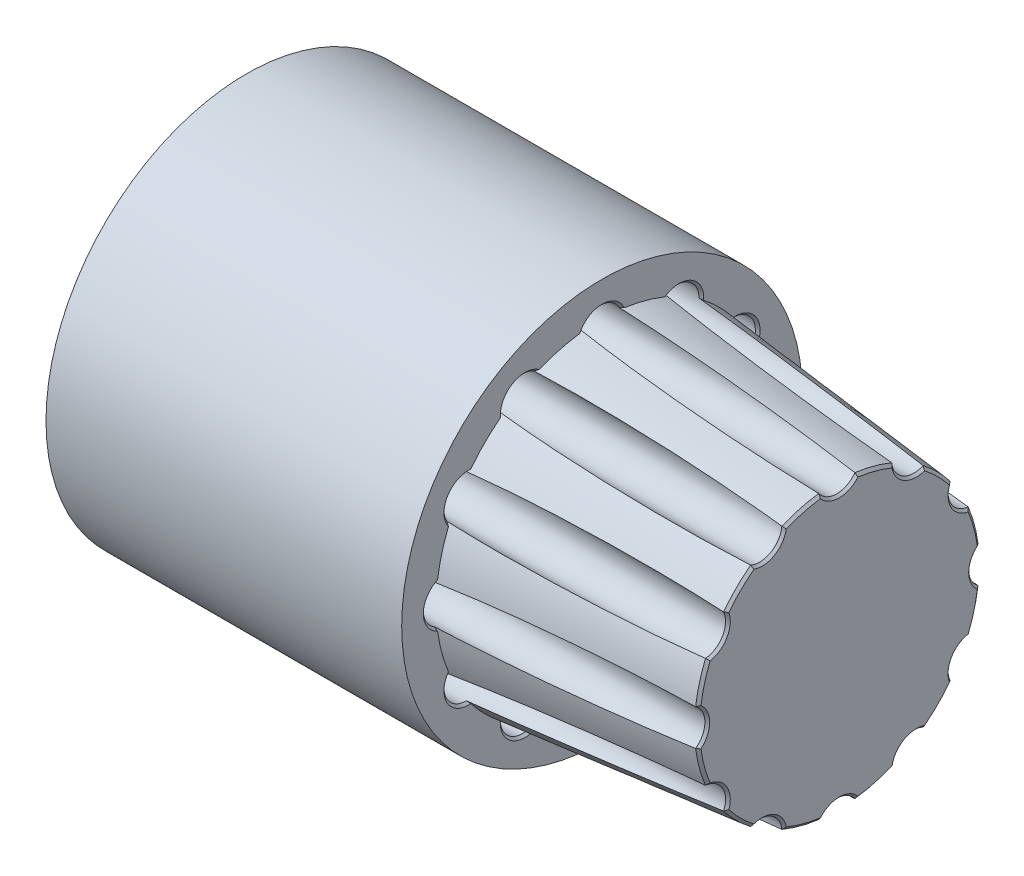
SolidWorks part; units mm, degrees
material "AISI 4340 Steel, normalized"
ref_plane "Front" through (0, 0, 0) normal (0, 0, 1) x (1, 0, 0)
ref_plane "Top" through (0, 0, 0) normal (0, 1, 0) x (1, 0, 0)
ref_plane "Right" through (0, 0, 0) normal (1, 0, 0) x (0, 0, -1)
sketch "Sketch1" plane through (0, 0, 0) normal (1, 0, 0) x (0, 0, -1)
  circle A0 centre (0, 0) radius 21.463
extrude "Extrude1" add sketch "Sketch1" along normal blind 38.1
sketch "Sketch2" plane through (38.1, 0, 0) normal (1, 0, 0) x (0, 0, -1)
  circle A0 centre (0, 0) radius 17.78
extrude "Extrude2" add sketch "Sketch2" along normal blind 25.4 draft 5.75
sketch "Sketch3" plane through (63.5, 0, 0) normal (1, 0, 0) x (0, 0, -1)
  point P0 (-16.51, 0)
hole_wizard "3/16 (0.1875) Diameter Hole1" positions "3DSketch1" profile "Sketch4" hole size "3/16" standard "Ansi Inch"
sketch3d "3DSketch1"
  point P0 (63.5, 0, 16.51)
sketch "Sketch4" plane through (63.5, 0, 16.51) normal (0, 1, 0) x (0, 0, -1)
  line L0 (0, 0) -> (0, 33.1808)
  line L1 (0, 33.1808) -> (2.3812, 31.75)
  line L2 (2.3812, 31.75) -> (2.3812, 0)
  line L5 (2.3812, 0) -> (0, 0)
  line L10 (0, 33.1808) -> (-2.3813, 31.75) construction
  line L11 (0, -6.35) -> (0, 107.95) construction
  dimension "Hole Dia." = 4.7625
  dimension "Hole Depth" = 31.75
  dimension "Drill Angle" = 118
pattern_circular "CirPattern1" count 12 over 360 about axis through (0, 0, 0) along (1, 0, 0) of "3/16 (0.1875) Diameter Hole1"
chamfer "Chamfer1" distance 0.254 angle 45 36 edges at (63.5, 10.7638, 10.7638) (63.5, 12.2359, 7.0644) (63.5, 14.7037, 3.9398) (63.5, 14.1288, 0) (63.5, 14.7037, -3.9398) (63.5, 12.2359, -7.0644) (63.5, 10.7638, -10.7638) (63.5, 7.0644, -12.2359) (63.5, 3.9398, -14.7037) (63.5, 0, -14.1288) (63.5, -3.9398, -14.7037) (63.5, -7.0644, -12.2359) (63.5, -10.7638, -10.7638) (63.5, -12.2359, -7.0644) (63.5, -14.7037, -3.9398) (63.5, -14.1288, 0) (63.5, -14.7037, 3.9398) (63.5, -12.2359, 7.0644) (63.5, -10.7638, 10.7638) (63.5, -7.0644, 12.2359) (63.5, -3.9398, 14.7037) (63.5, 0, 14.1288) (63.5, 3.9398, 14.7037) (63.5, 7.0644, 12.2359) (38.1, -9.4456, 16.3603) (38.1, 0, 18.8912) (38.1, 9.4456, 16.3603) (38.1, 16.3603, 9.4456) (38.1, 18.8912, 0) (38.1, 16.3603, -9.4456) (38.1, 9.4456, -16.3603) (38.1, 0, -18.8912) (38.1, -9.4456, -16.3603) (38.1, -16.3603, -9.4456) (38.1, -18.8912, 0) (38.1, -16.3603, 9.4456)
